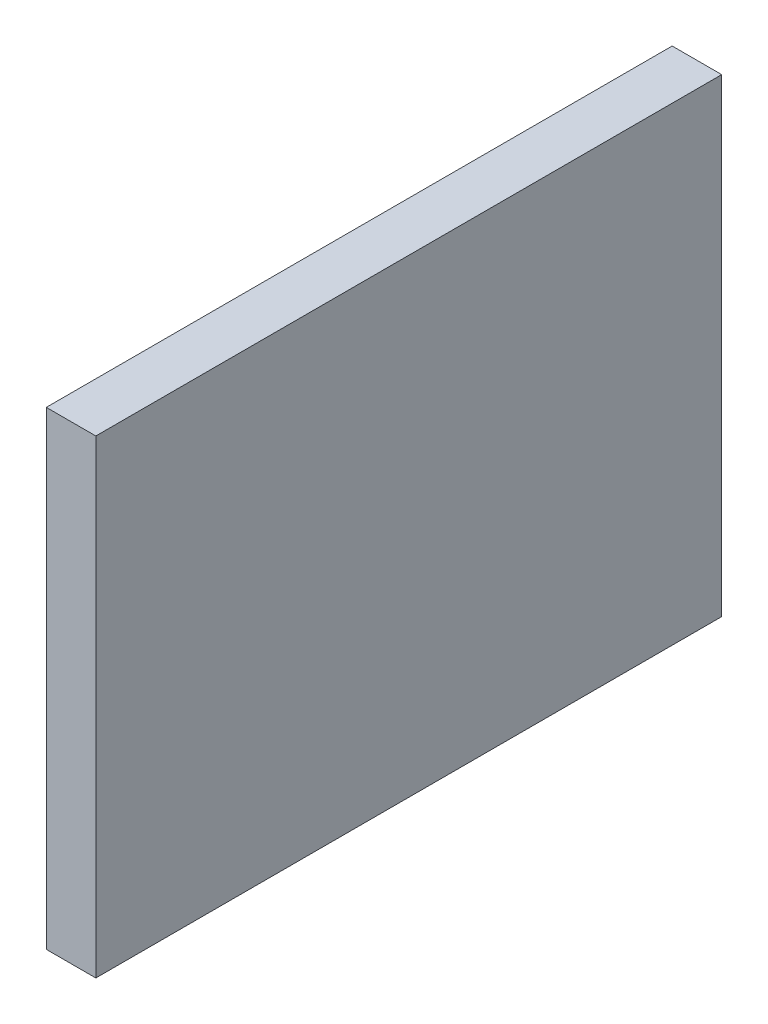
SolidWorks part; units mm, degrees
ref_plane "Front Plane" through (0, 0, 0) normal (0, 0, 1) x (1, 0, 0)
ref_plane "Top Plane" through (0, 0, 0) normal (0, 1, 0) x (1, 0, 0)
ref_plane "Right Plane" through (0, 0, 0) normal (1, 0, 0) x (0, 0, -1)
sketch "Sketch1" plane through (0, 0, 0) normal (1, 0, 0) x (0, 0, -1)
  line L1 (-60, -45) -> (60, -45)
  line L2 (-60, -45) -> (-60, 45)
  line L3 (-60, 45) -> (60, 45)
  line L4 (60, -45) -> (60, 45)
  line L5 (-60, -45) -> (60, 45) construction
  line L6 (-60, 45) -> (60, -45) construction
  point P0 (0, 0)
  dimension "D1" = 120
  dimension "D2" = 90
extrude "Boss-Extrude1" add sketch "Sketch1" along normal blind 9.5
